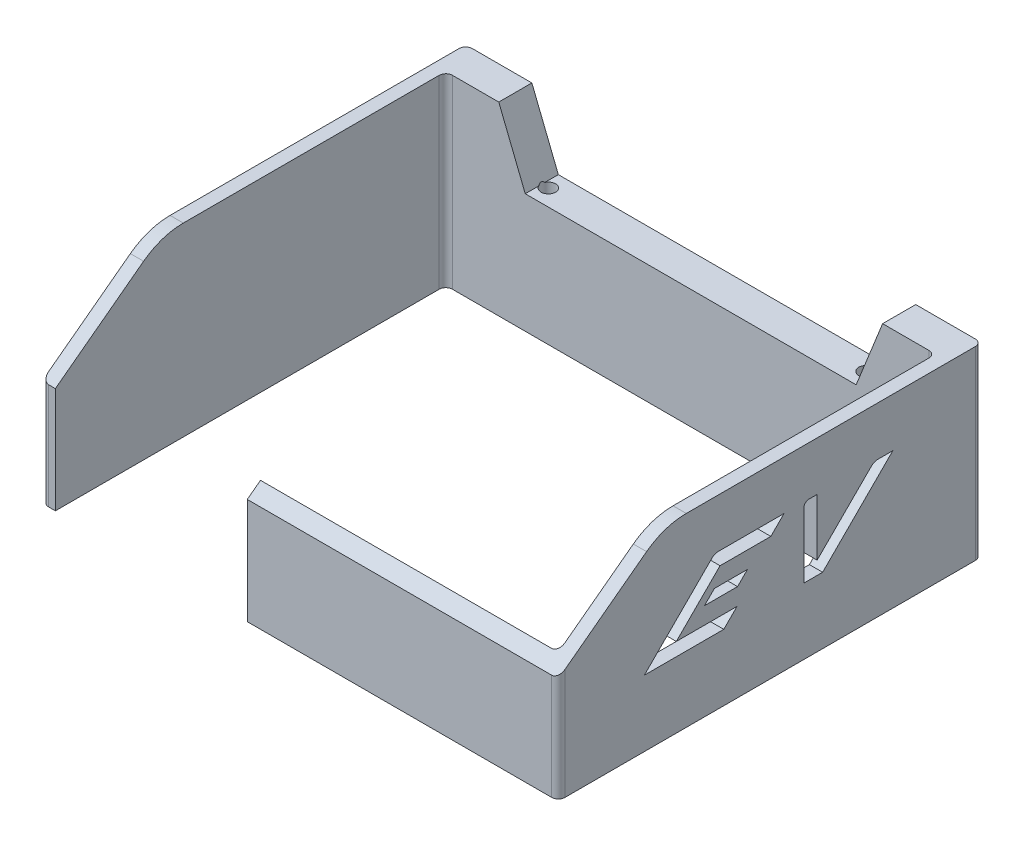
SolidWorks part; units mm, degrees
other "标注1"
sketch "草图7" plane through (39, 28, -33.5) normal (0.5459, 0.1206, -0.8291) x (-0.8365, 0.0219, -0.5476)
ref_plane "前视基准面" through (0, 0, 0) normal (0, 0, 1) x (1, 0, 0)
ref_plane "上视基准面" through (0, 0, 0) normal (0, 1, 0) x (1, 0, 0)
ref_plane "右视基准面" through (0, 0, 0) normal (1, 0, 0) x (0, 0, -1)
other "Configuration Table"
sketch "草图1" plane through (0, 0, 0) normal (0, 1, 0) x (1, 0, 0)
  line L0 (0, 0) -> (0, 54.085) construction
  line L1 (-39, -30.5) -> (39, -30.5)
  line L2 (-39, -30.5) -> (-39, 30.5)
  line L4 (39, -30.5) -> (39, 30.5)
  line L5 (-39, -30.5) -> (39, 30.5) construction
  line L6 (-39, 30.5) -> (39, -30.5) construction
  line L7 (-37, -28.5) -> (37, -28.5)
  line L8 (-37, -28.5) -> (-37, 28.5)
  line L9 (-37, 28.5) -> (37, 28.5)
  line L10 (37, -28.5) -> (37, 28.5)
  line L11 (-37, -28.5) -> (37, 28.5) construction
  line L12 (-37, 28.5) -> (37, -28.5) construction
  line L13 (39, 30.5) -> (-39, 30.5) construction
  line L14 (-39, 30.5) -> (-39, 33.5)
  line L15 (-39, 33.5) -> (39, 33.5)
  line L16 (39, 33.5) -> (39, 30.5)
  circle A0 centre (24, 31) radius 1.1
  circle A1 centre (-24, 31) radius 1.1
  point P0 (0, 0)
  point P6 (0, 0)
  dimension "D5" = 2.2
  dimension "D9" = 0
  dimension "D1" = 2
  dimension "D2" = 74
  dimension "D3" = 74
  dimension "D4" = 57
  dimension "D6" = 48
  dimension "D7" = 2.5
  dimension "D8" = 2
  dimension "D10" = 5
extrude "凸台-拉伸1" add sketch "草图1" along normal blind 28
sketch "草图2" plane through (0, 28, 0) normal (0, 1, 0) x (1, 0, 0)
  line L0 (0, 0) -> (0, -39.6677) construction
  line L1 (-39, -30.5) -> (39, -30.5) construction
  line L2 (-20, -37.5) -> (20, -37.5)
  line L3 (-20, -37.5) -> (-20, -23.5)
  line L4 (-20, -23.5) -> (20, -23.5)
  line L5 (20, -37.5) -> (20, -23.5)
  line L6 (-20, -37.5) -> (20, -23.5) construction
  line L7 (-20, -23.5) -> (20, -37.5) construction
  point P1 (0, -30.5)
  dimension "D1" = 40
  dimension "D2" = 14
extrude "切除-拉伸1" cut sketch "草图2" against normal blind 28
sketch "草图3" plane through (39, 0, 0) normal (1, 0, 0) x (0, 0, -1)
  line L0 (-30.5, 28) -> (-14.5, 28)
  line L1 (-30.5, 28) -> (33.5, 28) construction
  line L2 (-14.5, 28) -> (-30.5, 16)
  line L3 (-30.5, 28) -> (-30.5, 0) construction
  line L4 (-30.5, 16) -> (-30.5, 28)
  dimension "D1" = 16
  dimension "D2" = 12
extrude "切除-拉伸2" cut sketch "草图3" against normal through all
sketch "草图4" plane through (0, 28, 0) normal (0, 1, 0) x (1, 0, 0)
  line L0 (-37, -14.5) -> (-37, -36.5879)
  line L1 (-37, -36.5879) -> (-17, -36.5879)
  line L2 (-17, -36.5879) -> (-17, -15.9515)
  line L3 (-17, -15.9515) -> (-37, -14.5)
  dimension "D1" = 20
  dimension "D2" = 20
  dimension "D3" = 20.6364
  dimension "D4" = 22.0879
extrude "切除-拉伸5" cut sketch "草图4" against normal through all
sketch "草图5" plane through (20, 0, 0) normal (-1, 0, 0) x (0, 0, 1)
  line L4 (30.5, 0) -> (30.5, 16)
  line L5 (30.5, 16) -> (28.5, 17.5)
  line L6 (28.5, 17.5) -> (28.5, 0)
  line L7 (28.5, 0) -> (30.5, 0)
  line L8 (30.5, 0) -> (30.5, 16)
  line L9 (30.5, 16) -> (28.5, 17.5)
  line L10 (28.5, 17.5) -> (28.5, 0)
  line L11 (28.5, 0) -> (30.5, 0)
  dimension "D1" = 0
extrude "凸台-拉伸2" add sketch "草图5" along normal blind 28
fillet "圆角1" radius 1 4 edges at (-39, 8, 30.5) (-39, 14, -33.5) (39, 14, -33.5) (39, 8, 30.5)
fillet "圆角2" radius 1 3 edges at (37, 8.75, 28.5) (37, 14, -28.5) (-37, 14, -28.5)
fillet "圆角3" radius 10 2 edges at (-38, 28, 14.5) (38, 28, 14.5)
sketch "草图8" plane through (0, 0, -33.5) normal (0, 0, -1) x (-1, 0, 0)
  line L0 (0, 0) -> (0, 18) construction
  line L1 (-38, 0) -> (38, 0) construction
  line L2 (29, 28) -> (-29, 28)
  line L3 (-38, 28) -> (38, 28) construction
  line L4 (-29, 28) -> (-25, 18)
  line L5 (-25, 18) -> (25, 18)
  line L7 (29, 28) -> (25, 18)
  line L8 (0, 28) -> (0, 38.2044) construction
  line L9 (-39, 0) -> (-39, 28) construction
  dimension "D1" = 10
  dimension "D2" = 10
  dimension "D3" = 50
extrude "切除-拉伸6" cut sketch "草图8" against normal up to next
sketch "草图9" plane through (39, 0, 0) normal (1, 0, 0) x (0, 0, -1)
  line L0 (-7.308, 20.192) -> (-17.5, 10)
  line L1 (-17.5, 10) -> (-5.5, 10)
  line L2 (-5.5, 10) -> (-3.5, 12)
  line L3 (-3.5, 12) -> (-12.6716, 12)
  line L9 (-6.065, 18.6066) -> (1.6066, 18.6066)
  line L10 (1.6066, 18.6066) -> (3.6066, 20.6066)
  line L11 (3.6066, 20.6066) -> (-6.307, 20.6066)
  line L12 (6.6066, 19.8518) -> (6.6066, 10)
  line L44 (-6.065, 18.6066) -> (-12.6716, 12)
  line L45 (-29.5, 0) -> (32.5, 0) construction
  line L46 (-29.5, 16.75) -> (-29.5, 0) construction
  line L47 (-6.9212, 16.0533) -> (-8.4212, 14.5533)
  line L48 (-8.4212, 14.5533) -> (-3.4212, 14.5533)
  line L49 (-3.4212, 14.5533) -> (-1.9212, 16.0533)
  line L50 (-1.9212, 16.0533) -> (-6.9212, 16.0533)
  line L51 (-3.5, 18.6066) -> (-3.5, 16.0533) construction
  line L52 (-6.3441, 14.5533) -> (-6.3441, 12) construction
  line L53 (6.6066, 10) -> (9.435, 10)
  line L54 (9.435, 10) -> (20.0416, 20.6066)
  line L55 (20.0416, 20.6066) -> (17.7996, 20.6066)
  line L56 (16.7986, 20.192) -> (8.6066, 12)
  line L57 (8.6066, 12) -> (8.6066, 20.6066)
  line L58 (8.6066, 20.6066) -> (7.3614, 20.6066)
  arc A0 (-7.308, 20.192) -> (-6.307, 20.6066) centre (-6.307, 19.1909) cw
  arc A1 (7.3614, 20.6066) -> (6.6066, 19.8518) centre (7.3614, 19.8518) ccw
  arc A2 (16.7986, 20.192) -> (17.7996, 20.6066) centre (17.7996, 19.1909) cw
  point P14 (-4.4212, 16.0533)
  point P31 (8.0224, 19.4874)
  point P36 (9.0707, 18.2619)
  point P37 (17.8817, 19.0883)
  dimension "D18" = 10.6066
  dimension "D19" = 13.6844
  dimension "D20" = 0.7548
  dimension "D21" = 1.4157
  dimension "D22" = 1.4157
  dimension "D1" = 2
  dimension "D2" = 2
  dimension "D3" = 2
  dimension "D4" = 9.9136
  dimension "D5" = 45
  dimension "D6" = 12
  dimension "D7" = 10
  dimension "D8" = 12
  dimension "D9" = 1.5
  dimension "D10" = 1.2
  dimension "D11" = 5
  dimension "D12" = 3.7548
  dimension "D13" = 2
  dimension "D14" = 2
  dimension "D15" = 2
  dimension "D16" = 45
  dimension "D17" = 7.6716
extrude "切除-拉伸7" cut sketch "草图9" against normal up to next
